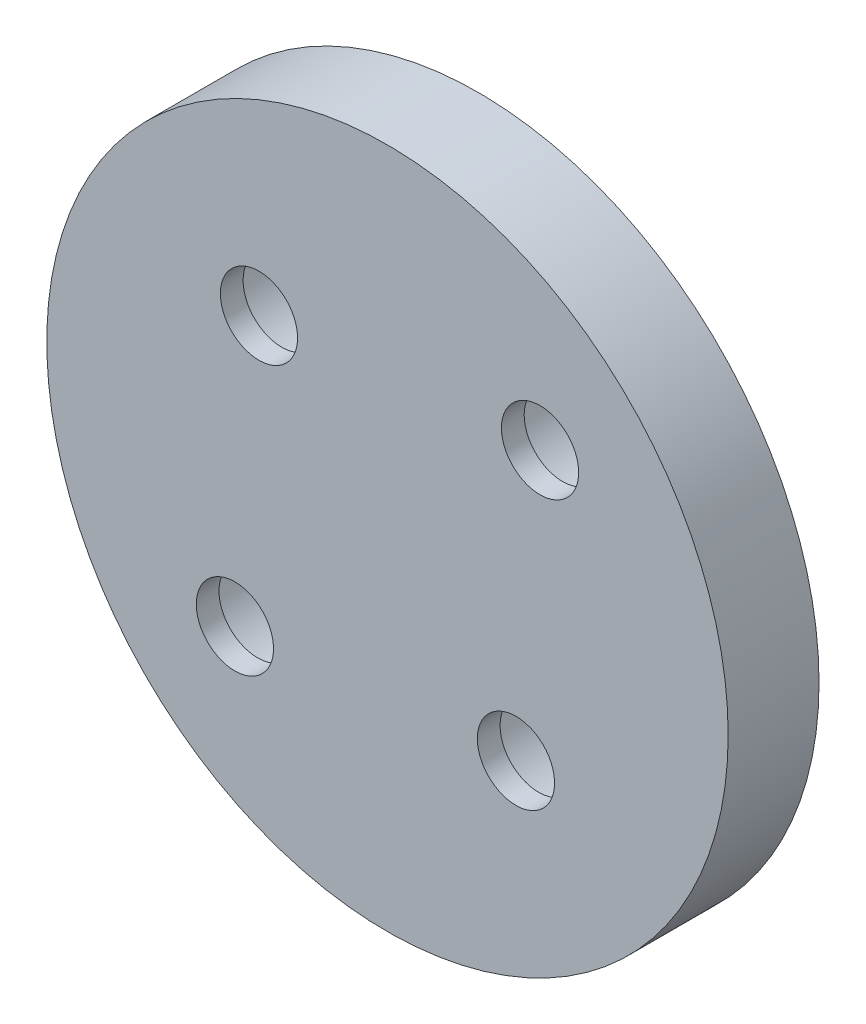
SolidWorks part; units mm, degrees
ref_plane "Front Plane" through (0, 0, 0) normal (0, 0, 1) x (1, 0, 0)
ref_plane "Top Plane" through (0, 0, 0) normal (0, 1, 0) x (1, 0, 0)
ref_plane "Right Plane" through (0, 0, 0) normal (1, 0, 0) x (0, 0, -1)
sketch "Sketch1" plane through (0, 0, 0) normal (0, 0, 1) x (1, 0, 0)
  circle A0 centre (0, 0) radius 15
  dimension "D1" = 30
extrude "Boss-Extrude1" add sketch "Sketch1" along normal blind 4
sketch "Sketch2" plane through (0, 0, 0) normal (0, 0, -1) x (-1, 0, 0)
  line L0 (-5.6569, -5.6569) -> (5.6569, 5.6569) construction
  line L1 (-6.7175, 6.7175) -> (6.7175, -6.7175) construction
  line L2 (0, 15) -> (0, -15) construction
  line L3 (-15, 0) -> (15, 0) construction
  circle A0 centre (-6.7175, 6.7175) radius 3.25
  circle A1 centre (6.7175, -6.7175) radius 3.25
  circle A2 centre (-5.6569, -5.6569) radius 3.25
  circle A3 centre (5.6569, 5.6569) radius 3.25
  circle A4 centre (0, 0) radius 15 construction
  dimension "D4" = 6.5
  dimension "D8" = 45
  dimension "D1" = 19
  dimension "D2" = 9.5
  dimension "D3" = 9.5
  dimension "D5" = 16
  dimension "D6" = 8
  dimension "D7" = 8
  dimension "D9" = 45
extrude "Cut-Extrude1" cut sketch "Sketch2" against normal blind 3
sketch "Sketch3" plane through (0, 0, 0) normal (0, 0, -1) x (-1, 0, 0)
  circle A0 centre (-6.7175, 6.7175) radius 1.7
  circle A1 centre (5.6569, 5.6569) radius 1.7
  circle A2 centre (6.7175, -6.7175) radius 1.7
  circle A3 centre (-5.6569, -5.6569) radius 1.7
  dimension "D1" = 3.4
extrude "Cut-Extrude2" cut sketch "Sketch3" against normal through all
ref_plane "Plane1" through (0, 0, 3) normal (0, 0, 1) x (1, 0, 0)
sketch "Sketch4" plane through (0, 0, 3) normal (0, 0, 1) x (1, 0, 0)
  circle A0 centre (0, 0) radius 2
  dimension "D1" = 4
extrude "Cut-Extrude3" cut sketch "Sketch4" against normal blind 2
sketch "Sketch5" plane through (0, 0, 0) normal (0, 0, 1) x (1, 0, 0)
  line L0 (0, 15) -> (0, -15) construction
  line L1 (1.5, 7.5) -> (-1.5, 7.5)
  line L2 (1.5, 7.5) -> (1.5, -7.5)
  line L3 (1.5, -7.5) -> (-1.5, -7.5)
  line L4 (-1.5, 7.5) -> (-1.5, -7.5)
  circle A0 centre (0, 0) radius 15 construction
  dimension "D1" = 3
  dimension "D2" = 1.5
  dimension "D3" = 15
  dimension "D4" = 7.5
extrude "Boss-Extrude2" add sketch "Sketch5" against normal blind 2
sketch "Sketch7" plane through (0, 0, 0) normal (0, 0, -1) x (-1, 0, 0)
  line L0 (1.5, -7.5) -> (-1.5, -7.5) construction
  line L1 (-1.5, 7.5) -> (-0.5, 7.5)
  line L2 (-1.5, 7.5) -> (-1.5, -7.5)
  line L3 (-1.5, -7.5) -> (-0.5, -7.5)
  line L4 (-0.5, 7.5) -> (-0.5, -7.5)
  line L5 (1.5, 7.5) -> (1.5, -7.5) construction
  line L6 (1.5, 7.5) -> (0.5, 7.5)
  line L7 (1.5, 7.5) -> (1.5, -7.5)
  line L8 (1.5, -7.5) -> (0.5, -7.5)
  line L9 (0.5, 7.5) -> (0.5, -7.5)
  line L10 (-1.5, 7.5) -> (1.5, 7.5) construction
  dimension "D1" = 1
extrude "Cut-Extrude4" cut sketch "Sketch7" along normal blind 1
